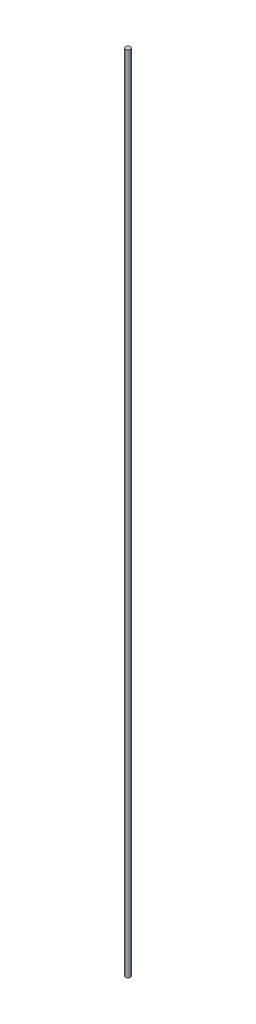
SolidWorks part; units mm, degrees
ref_plane "Front Plane" through (0, 0, 0) normal (0, 0, 1) x (1, 0, 0)
ref_plane "Top Plane" through (0, 0, 0) normal (0, 1, 0) x (1, 0, 0)
ref_plane "Right Plane" through (0, 0, 0) normal (1, 0, 0) x (0, 0, -1)
sketch "Sketch1" plane through (0, 0, 0) normal (0, 1, 0) x (1, 0, 0)
  circle A0 centre (0, 0) radius 0.11
  dimension "D1" = 0.22
extrude "Boss-Extrude1" add sketch "Sketch1" against normal offset from surface (37.57 mm away) 10 contours A0
sketch "Sketch3" plane through (0, 0, 0) normal (1, 0, 0) x (0, 0, -1)
  line L0 (-0.11, -37.57) -> (0.11, -37.1889)
  line L1 (0.11, -37.57) -> (0.11, 0) construction
  line L2 (0.11, -37.1889) -> (0.11, -37.57)
  line L3 (0.11, -37.57) -> (-0.11, -37.57)
  dimension "D1" = 60
extrude "Cut-Extrude1" [suppressed] cut sketch "Sketch3" against normal through all both and the other way through all
sketch "Sketch4" plane through (0, 0, 0) normal (0, 1, 0) x (1, 0, 0)
  line L1 (0, 0.11) -> (0, -0.11) construction
  circle A0 centre (0, 0) radius 0.11 construction
sketch "Sketch5" plane through (0, 0, 0) normal (1, 0, 0) x (0, 0, -1)
  line L0 (-0.11, -37.77) -> (0.11, -37.77) construction
  line L1 (-0.11, 0) -> (-0.11, -37.57) construction
  dimension "D1" = 0.2
